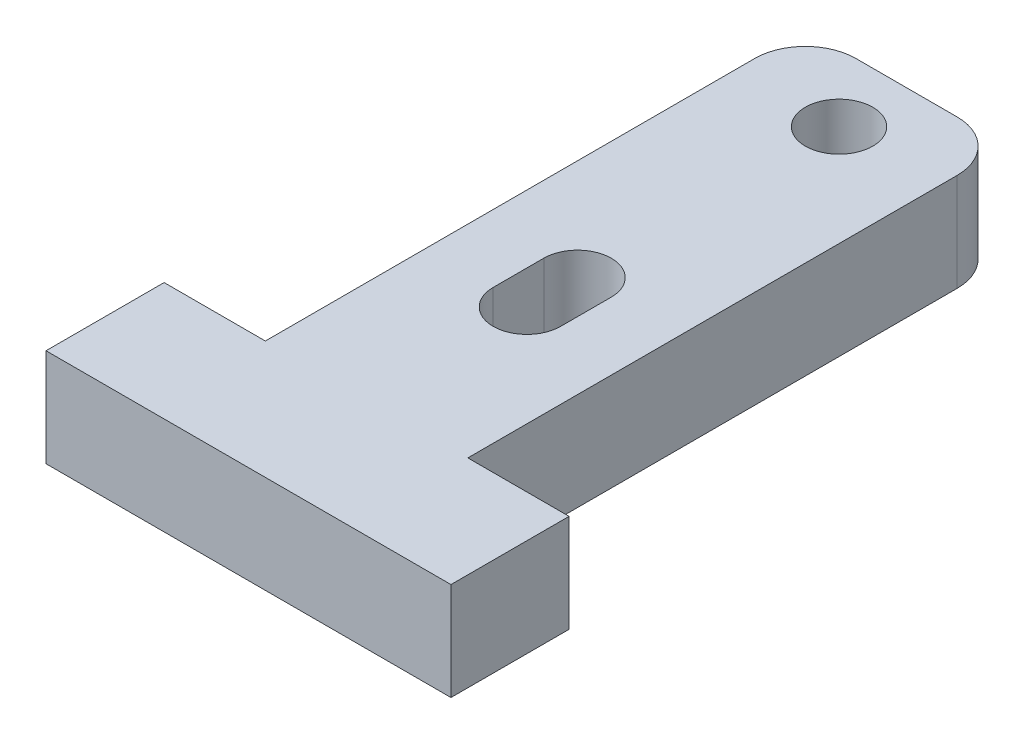
SolidWorks part; units mm, degrees
ref_plane "Front Plane" through (0, 0, 0) normal (0, 0, 1) x (1, 0, 0)
ref_plane "Top Plane" through (0, 0, 0) normal (0, 1, 0) x (1, 0, 0)
ref_plane "Right Plane" through (0, 0, 0) normal (1, 0, 0) x (0, 0, -1)
sketch "Sketch1" plane through (0, 0, 0) normal (0, 1, 0) x (1, 0, 0)
  line L0 (6, -18.6244) -> (12, -18.6244)
  line L1 (-3, 13.3756) -> (3, 13.3756)
  line L2 (-6, 10.3756) -> (-6, -18.6244)
  line L4 (6, 10.3756) -> (6, -18.6244)
  line L5 (0, -9.1244) -> (0, -6.1244) construction
  line L6 (-2, -9.1244) -> (-2, -6.1244)
  line L7 (-12, -18.6244) -> (-6, -18.6244)
  line L8 (-12, -18.6244) -> (-12, -25.6244)
  line L9 (-12, -25.6244) -> (12, -25.6244)
  line L10 (12, -18.6244) -> (12, -25.6244)
  line L11 (2, -9.1244) -> (2, -6.1244)
  arc A0 (-3, 13.3756) -> (-6, 10.3756) centre (-3, 10.3756) ccw
  arc A1 (3, 13.3756) -> (6, 10.3756) centre (3, 10.3756) cw
  circle A2 centre (0, 9.3756) radius 2
  arc A3 (-2, -9.1244) -> (2, -9.1244) centre (0, -9.1244) ccw
  arc A4 (2, -6.1244) -> (-2, -6.1244) centre (0, -6.1244) ccw
  point P0 (0, 0)
  point P6 (0, -19.5)
  point P14 (-6, 13.3756)
  point P17 (6, 13.3756)
  point P21 (0, -7.6244)
  dimension "D5" = 3
  dimension "D7" = 4
  dimension "D9" = 2
  dimension "D1" = 12
  dimension "D2" = 32
  dimension "D3" = 24
  dimension "D4" = 7
  dimension "D6" = 4
  dimension "D8" = 17
  dimension "D10" = 3
extrude "Boss-Extrude1" add sketch "Sketch1" along normal blind 5.8
